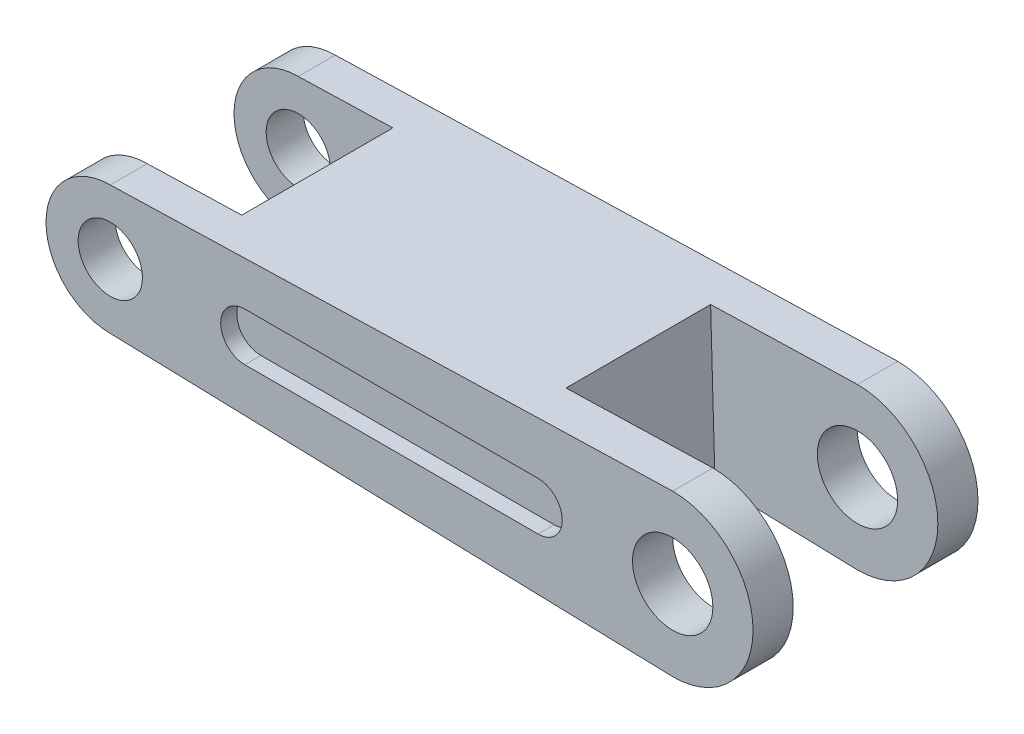
SolidWorks part; units mm, degrees
material "AISI 1020"
ref_plane "Front Plane" through (0, 0, 0) normal (0, 0, 1) x (1, 0, 0)
ref_plane "Top Plane" through (0, 0, 0) normal (0, 1, 0) x (1, 0, 0)
ref_plane "Right Plane" through (0, 0, 0) normal (1, 0, 0) x (0, 0, -1)
sketch "Sketch1" plane through (0, 0, 0) normal (0, 0, 1) x (1, 0, 0)
  line L0 (-175, 0) -> (175, 0) construction
  line L1 (-175, 40) -> (175, 50)
  line L2 (-175, -40) -> (175, -50)
  arc A0 (-175, 40) -> (-175, -40) centre (-175, 0) ccw
  arc A1 (172.1452, -49.9184) -> (172.1452, 49.9184) centre (175, 0) ccw
  circle A2 centre (175, 0) radius 25
  circle A3 centre (-175, 0) radius 20
  dimension "D1" = 80
  dimension "D2" = 100
  dimension "D4" = 50
  dimension "D5" = 40
  dimension "D3" = 350
extrude "Boss-Extrude1" add sketch "Sketch1" along normal mid plane 140
sketch "Sketch2" plane through (-1.2847, 44.9633, 0) normal (-0.0286, 0.9996, 0) x (0.9996, 0.0286, 0)
  line L0 (-114.9286, 47) -> (-214.9286, 47)
  line L1 (-214.9286, 70) -> (-214.9286, -70) construction
  line L2 (-114.9286, 47) -> (-114.9286, -47)
  line L3 (-114.9286, -47) -> (-214.9286, -47)
  line L4 (-173.7862, 70) -> (176.3566, 70) construction
  line L5 (84.9286, 45) -> (224.9286, 45)
  line L6 (-214.9286, 70) -> (-214.9286, -70) construction
  line L7 (-214.9286, 70) -> (-214.9286, 47) construction
  line L8 (-214.9286, -47) -> (-214.9286, -70) construction
  line L9 (-214.9286, 47) -> (-214.9286, -47)
  line L10 (224.9286, -70) -> (224.9286, 70) construction
  line L11 (224.9286, -70) -> (224.9286, 70) construction
  line L13 (84.9286, 45) -> (84.9286, -45)
  line L14 (84.9286, -45) -> (224.9286, -45)
  line L16 (224.9286, 45) -> (224.9286, -45)
  line L17 (173.5006, -70) -> (224.9286, -70) construction
  dimension "D1" = 23
  dimension "D2" = 23
  dimension "D3" = 100
  dimension "D4" = 25
  dimension "D5" = 140
  dimension "D6" = 25
extrude "Cut-Extrude1" cut sketch "Sketch2" against normal through all
sketch "Sketch3" plane through (-1.2847, 44.9633, 0) normal (-0.0286, 0.9996, 0) x (0.9996, 0.0286, 0)
  line L0 (-173.7862, -47) -> (-173.7862, 47) construction
  line L1 (-173.7862, -47) -> (-173.7862, 47)
  line L2 (-176.071, -47) -> (-176.071, 47) construction
  line L3 (-176.071, -47) -> (-176.071, 47)
  line L4 (-176.071, 47) -> (-173.7862, 47)
  line L5 (-176.071, -47) -> (-173.7862, -47)
extrude "Cut-Extrude4" cut sketch "Sketch3" against normal mid plane 90
sketch "Sketch4" plane through (0, 0, 70) normal (0, 0, 1) x (1, 0, 0)
  line L0 (-91.2811, 0) -> (91.2811, 0) construction
  line L1 (-91.2811, 15) -> (91.2811, 15)
  line L2 (-91.2811, -15) -> (91.2811, -15)
  arc A0 (-91.2811, 15) -> (-91.2811, -15) centre (-91.2811, 0) ccw
  arc A1 (91.2811, -15) -> (91.2811, 15) centre (91.2811, 0) ccw
  point P3 (0, 0)
  dimension "D1" = 15
  dimension "D2" = 182.5623
extrude "Cut-Extrude5" cut sketch "Sketch4" against normal blind 10
mirror "Mirror1" about plane through (0, 0, 0) normal (0, 0, 1) of "Cut-Extrude5"
